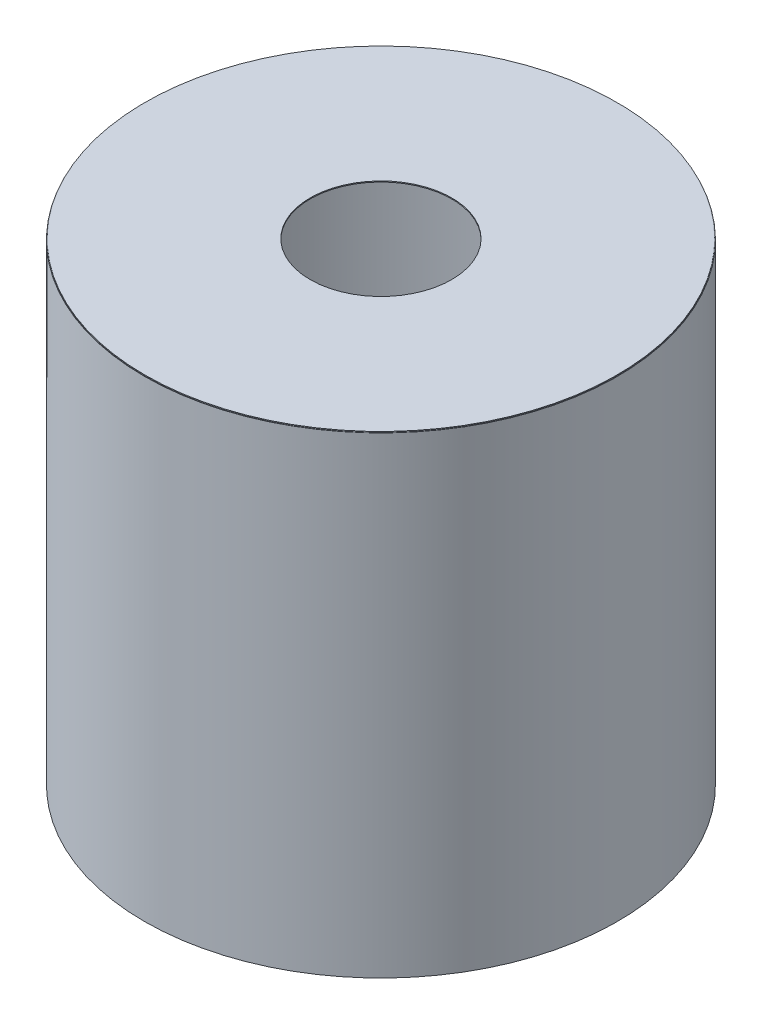
SolidWorks part; units mm, degrees
ref_plane "Front Plane" through (0, 0, 0) normal (0, 0, 1) x (1, 0, 0)
ref_plane "Top Plane" through (0, 0, 0) normal (0, 1, 0) x (1, 0, 0)
ref_plane "Right Plane" through (0, 0, 0) normal (1, 0, 0) x (0, 0, -1)
ref_plane "Plane1" through (0, 800, 0) normal (0, 1, 0) x (1, 0, 0)
sketch "Sketch1" plane through (0, 800, 0) normal (0, 1, 0) x (1, 0, 0)
  circle A0 centre (0, 0) radius 501
  circle A1 centre (0, 0) radius 500
extrude "Boss-Extrude1" add sketch "Sketch1" along normal blind 1000 contours A0 | A1
ref_plane "Plane2" through (0, 1800, 0) normal (0, 1, 0) x (1, 0, 0)
sketch "Sketch2" plane through (0, 1800, 0) normal (0, 1, 0) x (1, 0, 0)
  circle A0 centre (0, 0) radius 500
  circle A1 centre (0, 0) radius 150
extrude "Boss-Extrude2" add sketch "Sketch2" along normal blind 2 separate body
ref_plane "Plane3" through (0, 1200, 0) normal (0, 1, 0) x (1, 0, 0)
sketch "Sketch3" plane through (0, 1200, 0) normal (0, 1, 0) x (1, 0, 0)
  circle A0 centre (0, 0) radius 450
  circle A1 centre (0, 0) radius 100
extrude "Boss-Extrude3" add sketch "Sketch3" along normal blind 2 separate body
